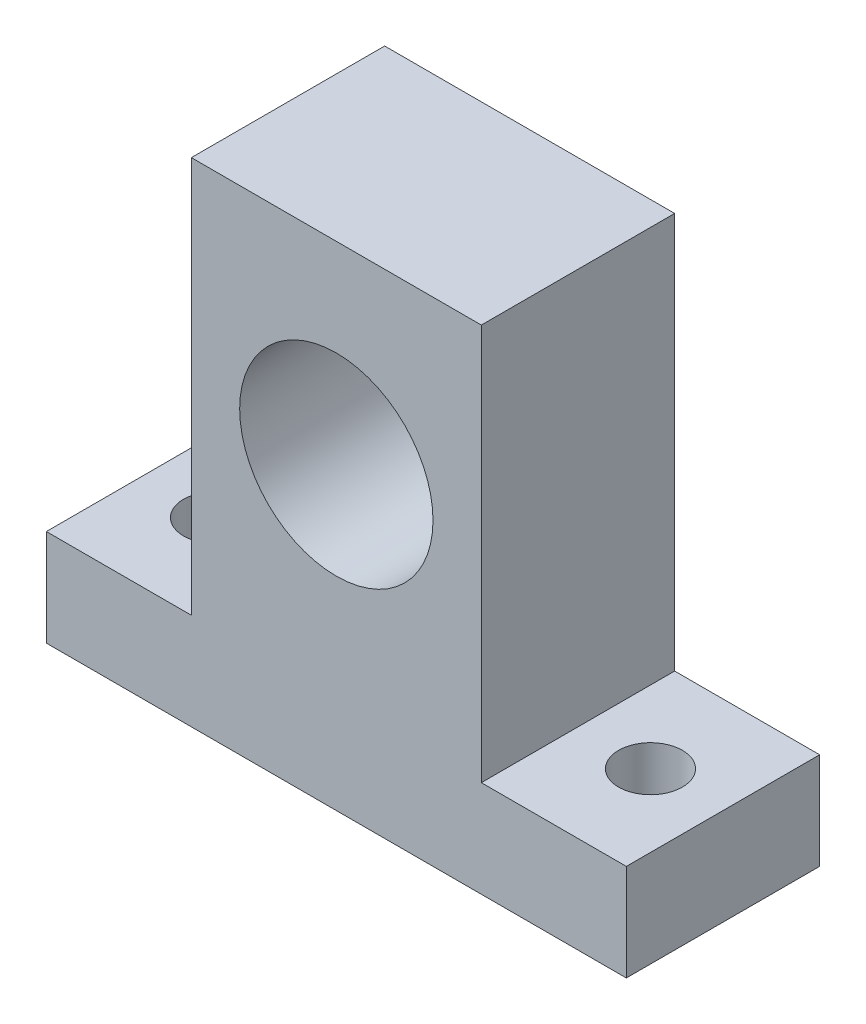
SolidWorks part; units mm, degrees
ref_plane "前视基准面" through (0, 0, 0) normal (0, 0, 1) x (1, 0, 0)
ref_plane "上视基准面" through (0, 0, 0) normal (0, 1, 0) x (1, 0, 0)
ref_plane "右视基准面" through (0, 0, 0) normal (1, 0, 0) x (0, 0, -1)
sketch "草图1" plane through (0, 0, 0) normal (0, 0, 1) x (1, 0, 0)
  line L0 (0, 58.08) -> (0, 0) construction
  line L1 (0, 0) -> (66.5383, 0) construction
  line L2 (-15, 51) -> (15, 51)
  line L3 (15, 51) -> (15, 10)
  line L4 (15, 10) -> (30, 10)
  line L5 (30, 10) -> (30, 0)
  line L6 (30, 0) -> (-30, 0)
  line L7 (-30, 10) -> (-30, 0)
  line L8 (-15, 10) -> (-30, 10)
  line L9 (-15, 51) -> (-15, 10)
  circle A0 centre (0, 31) radius 10
  point P10 (0, 51)
  dimension "D1" = 20
  dimension "D2" = 30
  dimension "D3" = 60
  dimension "D4" = 10
  dimension "D5" = 51
  dimension "D6" = 31
extrude "凸台-拉伸1" add sketch "草图1" along normal blind 20
sketch "草图2" plane through (0, 10, 0) normal (0, 1, 0) x (1, 0, 0)
  line L0 (-30, -10) -> (30, -10) construction
  line L1 (-30, -20) -> (-30, 0) construction
  line L2 (30, -20) -> (30, 0) construction
  line L3 (0, -10) -> (0, -29.5292) construction
  circle A0 centre (-22.5, -10) radius 3.3
  circle A1 centre (22.5, -10) radius 3.3
  dimension "D1" = 6.6
  dimension "D2" = 45
extrude "切除-拉伸1" cut sketch "草图2" against normal through all and the other way through all
